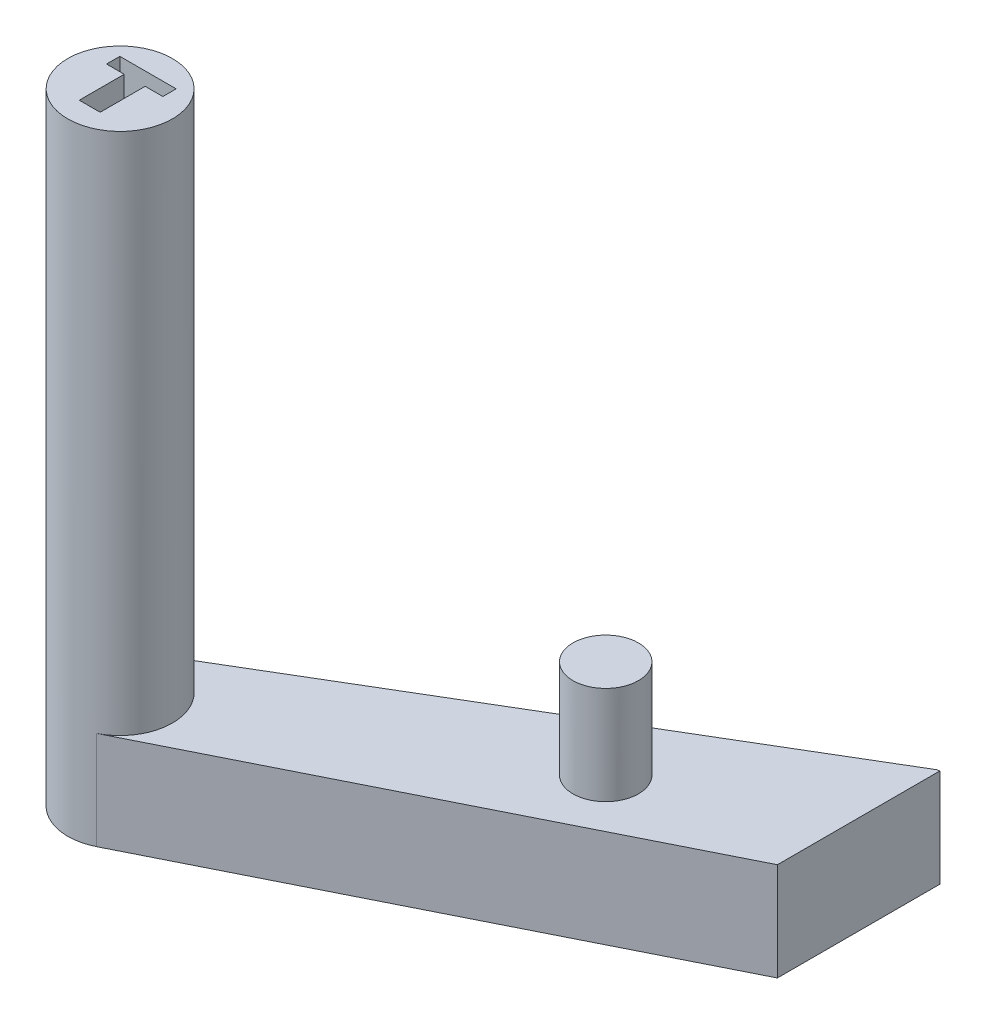
SolidWorks part; units mm, degrees
ref_plane "Front Plane" through (0, 0, 0) normal (0, 0, 1) x (1, 0, 0)
ref_plane "Top Plane" through (0, 0, 0) normal (0, 1, 0) x (1, 0, 0)
ref_plane "Right Plane" through (0, 0, 0) normal (1, 0, 0) x (0, 0, -1)
sketch "Sketch1" plane through (0, 0, 0) normal (0, 1, 0) x (1, 0, 0)
  circle A0 centre (0, 0) radius 8
extrude "Boss-Extrude1" add sketch "Sketch1" along normal blind 95 contours A0
sketch "Sketch2" plane through (0, 0, 0) normal (0, -1, 0) x (1, 0, 0)
  circle A0 centre (0, 0) radius 4
  dimension "D1" = 8
extrude "Cut-Extrude1" cut sketch "Sketch2" against normal blind 45
sketch "Sketch3" plane through (0, 95, 0) normal (0, 1, 0) x (1, 0, 0)
  line L0 (0, 10.5255) -> (0, -12.1183) construction
  line L1 (-12.2044, 0) -> (17.069, 0) construction
  line L3 (-4.3044, 4.2664) -> (4.3044, 4.2664)
  line L4 (-4.3044, 4.2664) -> (-4.3044, 2.2313)
  line L5 (-4.3044, 2.2313) -> (4.3044, 2.2313)
  line L6 (4.3044, 4.2664) -> (4.3044, 2.2313)
  line L7 (-4.3044, 4.2664) -> (4.3044, 2.2313) construction
  line L8 (-4.3044, 2.2313) -> (4.3044, 4.2664) construction
  line L9 (-1.5981, -4.6441) -> (1.5981, -4.6441)
  line L10 (-1.5981, -4.6441) -> (-1.5981, 2.2313)
  line L11 (-1.5981, 2.2313) -> (1.5981, 2.2313)
  line L12 (1.5981, -4.6441) -> (1.5981, 2.2313)
  line L13 (-1.5981, -4.6441) -> (1.5981, 2.2313) construction
  line L14 (-1.5981, 2.2313) -> (1.5981, -4.6441) construction
  point P5 (0, 3.2489)
  point P10 (0, -1.2064)
extrude "Cut-Extrude2" cut sketch "Sketch3" against normal blind 40 contours L9 L12 L11 L10 | L4 L5 L6 L3
sketch "Sketch4" plane through (0, 0, 0) normal (0, -1, 0) x (1, 0, 0)
  line L0 (-23.5273, 0) -> (50.3791, 0) construction
  line L1 (75.0017, -52.4967) -> (75.0017, -27.4967)
  line L2 (0, 0) -> (75.0017, -39.9967) construction
  line L3 (73.0017, -52.4967) -> (73.0017, -27.4967)
  line L4 (73.0017, -27.4967) -> (3.5728, 7.1579)
  line L5 (73.0017, -52.4967) -> (-5.4229, -5.8815)
  circle A0 centre (75.0017, -39.9967) radius 12.5
  circle A1 centre (0, 0) radius 8 construction
  circle A2 centre (0, 0) radius 8
  dimension "D3" = 2
  dimension "D4" = 25
  dimension "D1" = 28.07
  dimension "D2" = 85
extrude "Boss-Extrude2" add sketch "Sketch4" against normal blind 15
sketch "Sketch5" plane through (0, 15, 0) normal (0, 1, 0) x (1, 0, 0)
  line L0 (73.0017, 39.9162) -> (0, 0) construction
  line L1 (73.0017, 52.3357) -> (73.0017, 27.4967) construction
  circle A0 centre (0, 0) radius 8
  circle A1 centre (48.0017, 26.2466) radius 5
  dimension "D1" = 10
  dimension "D2" = 25
extrude "Boss-Extrude3" add sketch "Sketch5" along normal blind 15 contours A1 L0 | L0 A1 | A0
sketch "Sketch8" plane through (0, 45, 0) normal (0, -1, 0) x (1, 0, 0)
  line L0 (-2.7607, 2.8946) -> (0, 0) construction
  circle A0 centre (0, 0) radius 4 construction
ref_plane "Plane2" through (0, 0, 0) normal (-0.7236, 0, -0.6902) x (0.6902, 0, -0.7236)
sketch "Sketch9" plane through (0, 0, 0) normal (-0.7236, 0, -0.6902) x (0.6902, 0, -0.7236)
  line L0 (-4, -45) -> (0, -45)
  line L1 (0, -45) -> (0, -51.9282)
  line L2 (0, -51.9282) -> (-4, -45)
  dimension "D1" = 30
revolve "Cut-Revolve2" cut sketch "Sketch9" angle 360 about L1
